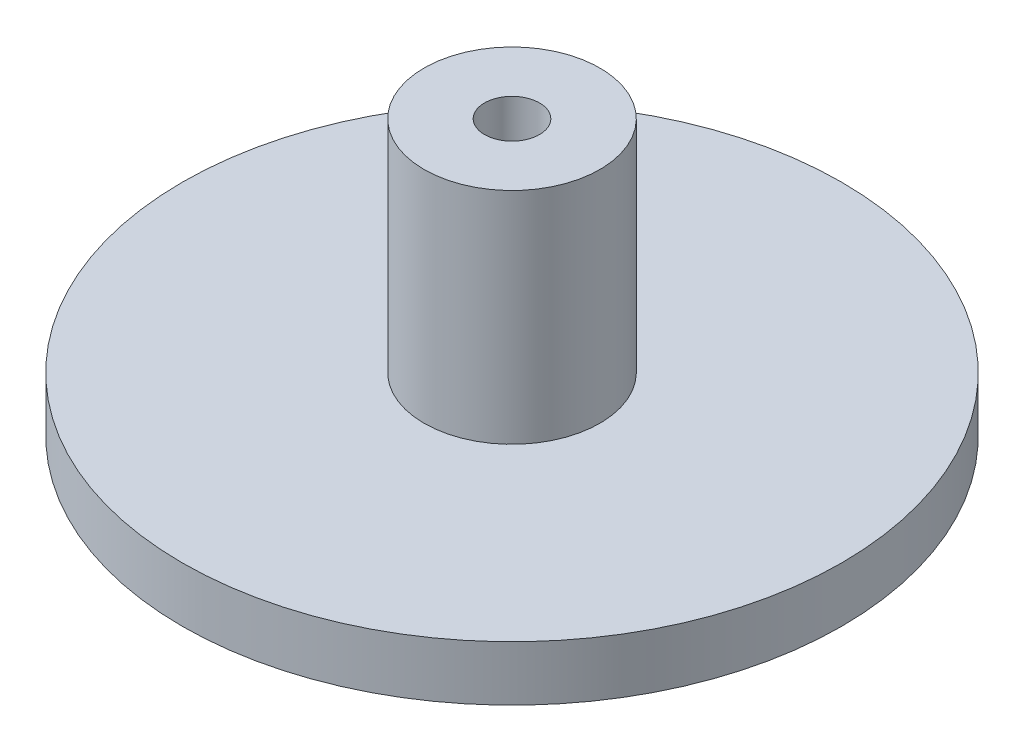
SolidWorks part; units mm, degrees
ref_plane "Front Plane" through (0, 0, 0) normal (0, 0, 1) x (1, 0, 0)
ref_plane "Top Plane" through (0, 0, 0) normal (0, 1, 0) x (1, 0, 0)
ref_plane "Right Plane" through (0, 0, 0) normal (1, 0, 0) x (0, 0, -1)
sketch "Sketch1" plane through (0, 0, 0) normal (0, 1, 0) x (1, 0, 0)
  circle A0 centre (0, 0) radius 30
  dimension "D1" = 60
extrude "Boss-Extrude1" add sketch "Sketch1" along normal blind 5
sketch "Sketch2" plane through (0, 5, 0) normal (0, 1, 0) x (1, 0, 0)
  circle A0 centre (0, 0) radius 8
extrude "Boss-Extrude2" add sketch "Sketch2" along normal blind 20
sketch "Sketch3" plane through (0, 25, 0) normal (0, 1, 0) x (1, 0, 0)
  circle A0 centre (0, 0) radius 2.5
  dimension "D1" = 5
extrude "Cut-Extrude1" cut sketch "Sketch3" against normal through all
